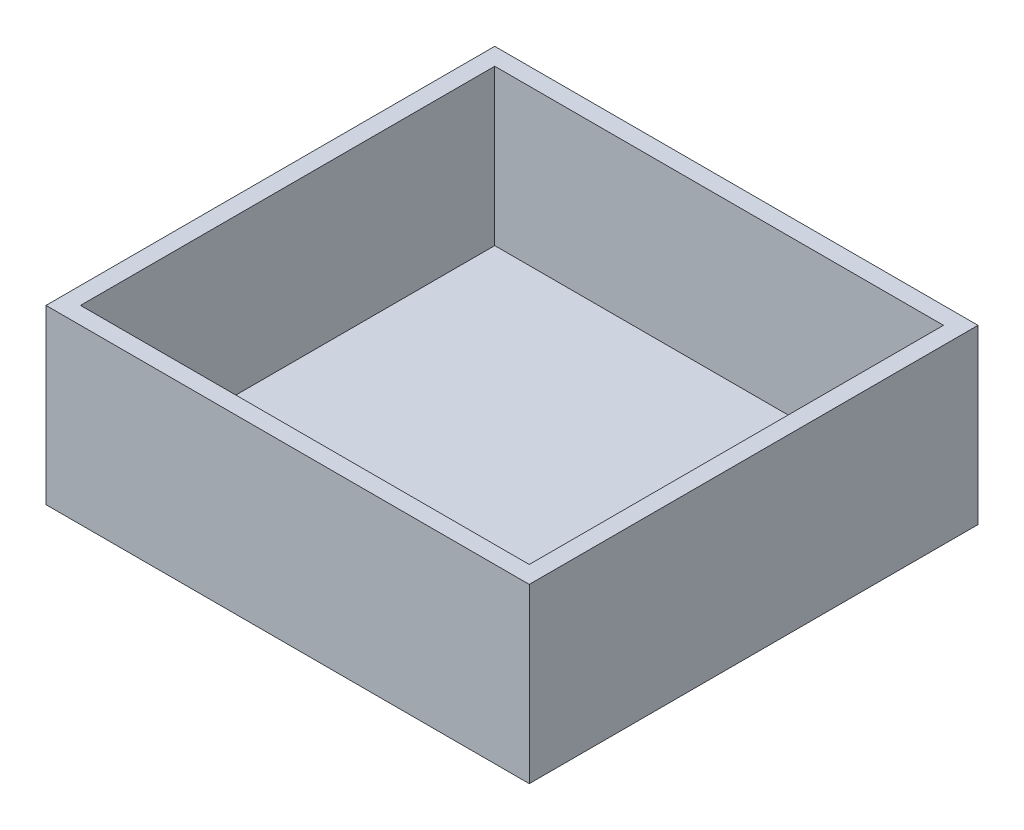
SolidWorks part; units mm, degrees
ref_plane "前基準面" through (0, 0, 0) normal (0, 0, 1) x (1, 0, 0)
ref_plane "上基準面" through (0, 0, 0) normal (0, 1, 0) x (1, 0, 0)
ref_plane "右基準面" through (0, 0, 0) normal (1, 0, 0) x (0, 0, -1)
sketch "草圖1" plane through (0, 0, 0) normal (0, 1, 0) x (1, 0, 0)
  line L1 (-70, 65) -> (70, 65)
  line L2 (-70, 65) -> (-70, -65)
  line L3 (-70, -65) -> (70, -65)
  line L4 (70, 65) -> (70, -65)
  line L5 (-70, 65) -> (70, -65) construction
  line L6 (-70, -65) -> (70, 65) construction
  point P0 (0, 0)
  dimension "D1" = 140
  dimension "D2" = 130
extrude "填料-伸長2" add sketch "草圖1" along normal mid plane 50
sketch "草圖4" plane through (0, 25, 0) normal (0, 1, 0) x (1, 0, 0)
  line L6 (-65, 60) -> (65, 60)
  line L7 (-65, 60) -> (-65, -60)
  line L8 (-65, -60) -> (65, -60)
  line L9 (65, 60) -> (65, -60)
  line L10 (-65, 60) -> (65, -60) construction
  line L11 (-65, -60) -> (65, 60) construction
  point P0 (0, 0)
  dimension "D2" = 130
  dimension "D1" = 120
extrude "除料-伸長1" cut sketch "草圖4" against normal blind 45
sketch "草圖5" plane through (0, -20, 0) normal (0, 1, 0) x (1, 0, 0)
  line L5 (65, 60) -> (-65, 60) construction
  line L6 (-65, 60) -> (-65, -60) construction
  line L7 (-1000, 0) -> (49000, 0) construction
  line L8 (0, 0) -> (0, -97.4829) construction
  line L9 (0, 0) -> (0, 121.4193) construction
  line L10 (0, 0) -> (70, 65) construction
  line L11 (-65, -60) -> (65, -60) construction
  line L12 (-94.2135, -87.4839) -> (91.6561, 85.1093) construction
  line L13 (65, -60) -> (65, 60) construction
  circle A0 centre (-58, 53) radius 5
  circle A3 centre (58, -53) radius 5
  dimension "D1" = 10
  dimension "D2" = 7
  dimension "D4" = 10
  dimension "D3" = 7
  dimension "D5" = 7
  dimension "D6" = 7
